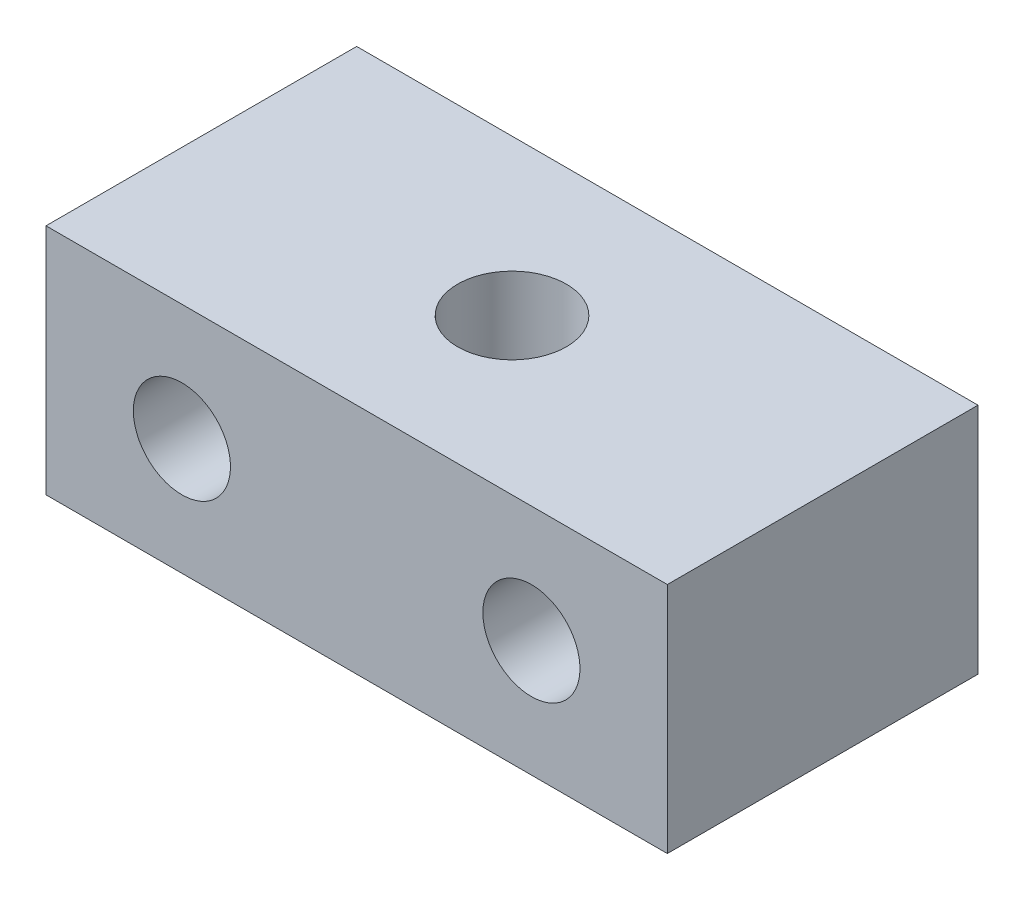
SolidWorks part; units mm, degrees
material "AISI Type A2 Tool Steel"
ref_plane "Front Plane" through (0, 0, 0) normal (0, 0, 1) x (1, 0, 0)
ref_plane "Top Plane" through (0, 0, 0) normal (0, 1, 0) x (1, 0, 0)
ref_plane "Right Plane" through (0, 0, 0) normal (1, 0, 0) x (0, 0, -1)
sketch "Sketch1" plane through (0, 0, 0) normal (0, 0, 1) x (1, 0, 0)
  line L0 (55, 0) -> (-55, 0) construction
  line L1 (-25.4, 9.525) -> (25.4, 9.525)
  line L2 (-25.4, 9.525) -> (-25.4, -9.525)
  line L3 (-25.4, -9.525) -> (25.4, -9.525)
  line L4 (25.4, 9.525) -> (25.4, -9.525)
  line L5 (-25.4, 9.525) -> (25.4, -9.525) construction
  line L6 (-25.4, -9.525) -> (25.4, 9.525) construction
  line L7 (0, -55) -> (0, 55) construction
  circle A0 centre (-14.2875, 0) radius 3.9687
  circle A1 centre (14.2875, 0) radius 3.9688
  point P0 (0, 0)
  dimension "D5" = 7.9375
  dimension "D1" = 50.8
  dimension "D2" = 19.05
  dimension "D3" = 28.575
  dimension "D4" = 14.2875
extrude "Boss-Extrude1" add sketch "Sketch1" along normal mid plane 25.4
sketch "Sketch2" plane through (0, 9.525, 0) normal (0, 1, 0) x (1, 0, 0)
  circle A0 centre (0, 0) radius 4.445
  dimension "D1" = 8.89
extrude "Cut-Extrude1" cut sketch "Sketch2" against normal through all
